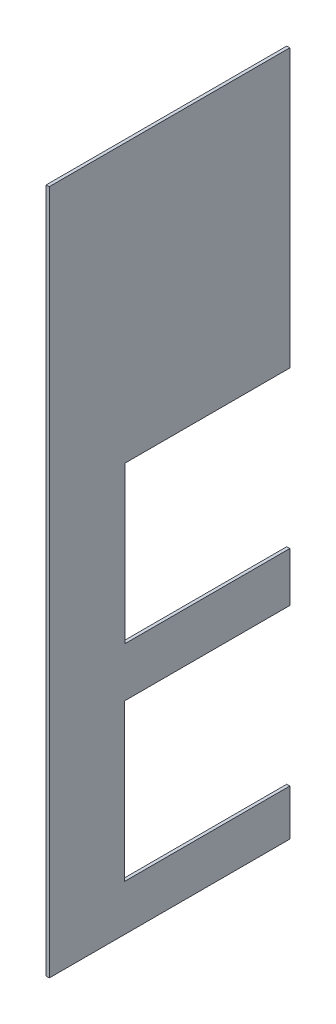
SolidWorks part; units mm, degrees
ref_plane "Спереди" through (0, 0, 0) normal (0, 0, 1) x (1, 0, 0)
ref_plane "Сверху" through (0, 0, 0) normal (0, 1, 0) x (1, 0, 0)
ref_plane "Справа" through (0, 0, 0) normal (1, 0, 0) x (0, 0, -1)
ref_plane "Плоскость4" through (0.5, 0, 0) normal (-1, 0, 0) x (0, -1, 0)
sketch "Эскиз1" plane through (0.5, 0, 0) normal (-1, 0, 0) x (0, -1, 0)
  line L0 (9.85, 42.25) -> (-100.85, 42.25)
  line L1 (-100.85, 42.25) -> (-100.85, 3.4)
  line L2 (-100.85, 3.4) -> (9.85, 3.4)
  line L3 (9.85, 3.4) -> (9.85, 42.25)
extrude "Бобышка-Вытянуть1" add sketch "Эскиз1" against normal blind 0.5
sketch "Эскиз3" plane through (0.5, 0, 0) normal (-1, 0, 0) x (0, 0, 1)
  line L1 (30.0066, 30.8071) -> (-3.688, 30.8071)
  line L2 (30.0066, 30.8071) -> (30.0066, 56.0571)
  line L3 (30.0066, 56.0571) -> (-3.688, 56.0571)
  line L4 (-3.688, 30.8071) -> (-3.688, 56.0571)
  line L8 (30.1066, -2.4179) -> (-3.688, -2.4179)
  line L9 (30.1066, -2.4179) -> (30.1066, 22.8321)
  line L10 (30.1066, 22.8321) -> (-3.688, 22.8321)
  line L11 (-3.688, -2.4179) -> (-3.688, 22.8321)
extrude "Вырез-Вытянуть1" cut sketch "Эскиз3" against normal through all
